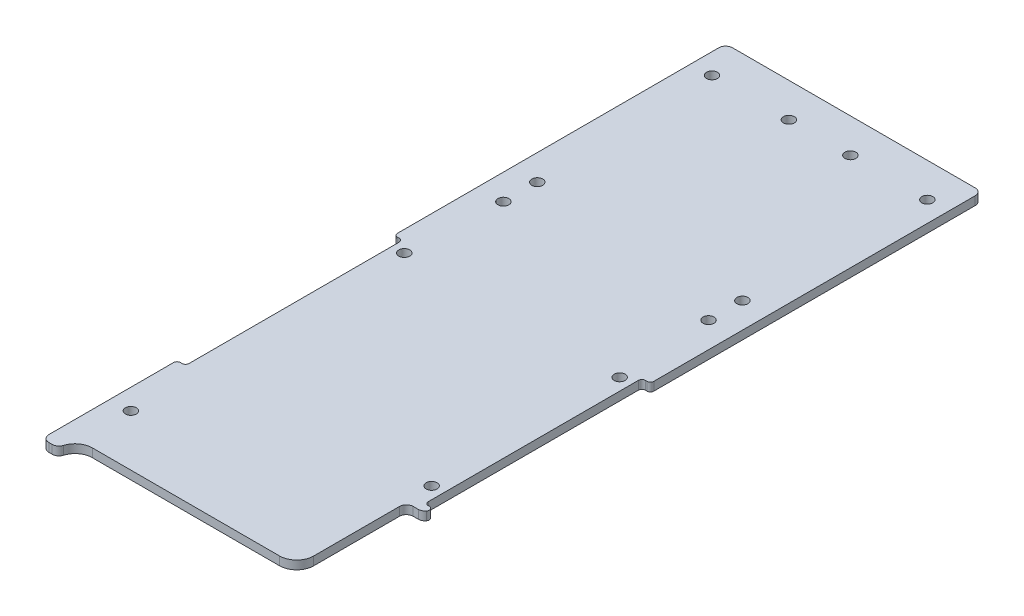
SolidWorks part; units mm, degrees
ref_plane "Front Plane" through (0, 0, 0) normal (0, 0, 1) x (1, 0, 0)
ref_plane "Top Plane" through (0, 0, 0) normal (0, 1, 0) x (1, 0, 0)
ref_plane "Right Plane" through (0, 0, 0) normal (1, 0, 0) x (0, 0, -1)
sketch "Sketch1" plane through (0, 0, 0) normal (0, 1, 0) x (1, 0, 0)
  line L0 (-39.9997, 0) -> (-39.9997, 114.3) construction
  line L1 (-47.625, 127) -> (47.625, 127)
  line L2 (-47.625, 127) -> (-47.625, -127)
  line L3 (-47.625, -127) -> (47.625, -127)
  line L4 (47.625, 127) -> (47.625, -127)
  line L5 (-47.625, 127) -> (47.625, -127) construction
  line L6 (-47.625, -127) -> (47.625, 127) construction
  line L7 (0, 0) -> (0, 127) construction
  line L8 (-39.9997, 0) -> (-39.9997, -101.6) construction
  line L9 (-39.9997, 0) -> (0, 0) construction
  line L10 (-41.275, -127) -> (-41.275, -120.65)
  line L11 (-41.275, -120.65) -> (41.275, -120.65)
  line L12 (41.275, -120.65) -> (41.275, -127)
  line L13 (-39.9997, 114.3) -> (-11.4247, 114.3) construction
  line L14 (39.9997, 114.3) -> (11.4247, 114.3) construction
  circle A0 centre (-39.9997, 114.3) radius 2.032
  circle A1 centre (-39.9997, 0) radius 2.032
  circle A2 centre (-39.9997, -101.6) radius 2.032
  circle A3 centre (39.9997, -101.6) radius 2.032
  circle A4 centre (39.9997, 0) radius 2.032
  circle A5 centre (39.9997, 114.3) radius 2.032
  circle A6 centre (-11.4247, 114.3) radius 2.032
  circle A7 centre (11.4247, 114.3) radius 2.032
  circle A8 centre (-39.9997, -69.85) radius 2.032
  circle A9 centre (39.9997, -69.85) radius 2.032
  point P0 (0, 0)
  dimension "D4" = 4.064
  dimension "D10" = 28.575
  dimension "D1" = 95.25
  dimension "D2" = 254
  dimension "D3" = 7.6253
  dimension "D5" = 12.7
  dimension "D6" = 25.4
  dimension "D7" = 6.35
  dimension "D8" = 6.35
  dimension "D9" = 6.35
  dimension "D11" = 69.85
extrude "Boss-Extrude1" add sketch "Sketch1" along normal blind 3.175 contours L4 L1 L2 L3 A4 A0 A1 A2 A3 A5 | A8 | A3
fillet "Fillet1" radius 2.54 4 edges at (-47.625, 1.5875, -127) (47.625, 1.5875, -127) (47.625, 1.5875, 127) (-47.625, 1.5875, 127)
fillet "Fillet2" radius 2.54 2 edges at (41.275, 1.5875, 127) (-41.275, 1.5875, 127)
fillet "Fillet3" radius 6.35 2 edges at (41.275, 1.5875, 120.65) (-41.275, 1.5875, 120.65)
sketch "Sketch2" plane through (0, 0, 0) normal (0, -1, 0) x (1, 0, 0)
  line L1 (43.815, 127) -> (45.085, 127) construction
  line L2 (40.6451, 123.5787) -> (40.6451, 79.8881)
  line L3 (40.6451, 79.8881) -> (47.625, 79.8881)
  line L11 (47.625, -124.46) -> (47.625, 124.46) construction
  line L12 (43.815, 127) -> (45.085, 127)
  line L13 (47.625, 79.8881) -> (47.625, 124.46)
  arc A0 (35.2956, 120.65) -> (41.3809, 125.1857) centre (35.2956, 127) ccw construction
  arc A1 (43.815, 127) -> (41.3809, 125.1857) centre (43.815, 124.46) ccw construction
  arc A2 (47.625, 124.46) -> (45.085, 127) centre (45.085, 124.46) ccw construction
  arc A3 (40.6451, 123.5787) -> (41.3809, 125.1857) centre (35.2956, 127) ccw
  arc A4 (43.815, 127) -> (41.3809, 125.1857) centre (43.815, 124.46) ccw
  arc A5 (47.625, 124.46) -> (45.085, 127) centre (45.085, 124.46) ccw
  dimension "D2" = 47.1119
  dimension "D1" = 6.9799
extrude "Cut-Extrude1" cut sketch "Sketch2" against normal through all contours L12 A5 L13 L3 L2 A3 A4
fillet "Fillet4" radius 6.35 1 edges at (40.6451, 1.5875, 123.5787)
fillet "Fillet5" radius 2.54 2 edges at (47.625, 1.5875, 79.8881) (40.6451, 1.5875, 79.8881)
sketch "Sketch3" plane through (0, 0, 0) normal (0, -1, 0) x (1, 0, 0)
  line L0 (-36.3001, -49.7791) -> (-39.9069, -49.7791) construction
  line L1 (-40.4149, -49.276) -> (-40.4149, -45.7043) construction
  line L2 (-35.7921, -45.7043) -> (-35.7921, -49.276) construction
  line L3 (-39.9069, -45.2013) -> (-36.3001, -45.2013) construction
  line L4 (-36.3001, -37.2027) -> (-39.9069, -37.2027) construction
  line L5 (-35.7921, -33.1279) -> (-35.7921, -36.6996) construction
  line L6 (-40.4149, -36.6996) -> (-40.4149, -33.1279) construction
  line L7 (-39.9069, -32.6249) -> (-36.3001, -32.6249) construction
  line L8 (36.2931, -32.6249) -> (39.8999, -32.6249) construction
  line L9 (40.4079, -33.1279) -> (40.4079, -36.6996) construction
  line L10 (39.8999, -37.2027) -> (36.2931, -37.2027) construction
  line L11 (35.7851, -36.6996) -> (35.7851, -33.1279) construction
  line L12 (36.2931, -45.2013) -> (39.8999, -45.2013) construction
  line L13 (35.7851, -49.276) -> (35.7851, -45.7043) construction
  line L14 (40.4079, -45.7043) -> (40.4079, -49.276) construction
  line L15 (39.8999, -49.7791) -> (36.2931, -49.7791) construction
  line L16 (-36.3001, -49.7791) -> (-39.9069, -49.7791)
  line L17 (-40.4149, -49.276) -> (-40.4149, -45.7043)
  line L18 (-35.7921, -45.7043) -> (-35.7921, -49.276)
  line L19 (-39.9069, -45.2013) -> (-36.3001, -45.2013)
  line L20 (-36.3001, -37.2027) -> (-39.9069, -37.2027)
  line L21 (-35.7921, -33.1279) -> (-35.7921, -36.6996)
  line L22 (-40.4149, -36.6996) -> (-40.4149, -33.1279)
  line L23 (-39.9069, -32.6249) -> (-36.3001, -32.6249)
  line L24 (36.2931, -32.6249) -> (39.8999, -32.6249)
  line L25 (40.4079, -33.1279) -> (40.4079, -36.6996)
  line L26 (39.8999, -37.2027) -> (36.2931, -37.2027)
  line L27 (35.7851, -36.6996) -> (35.7851, -33.1279)
  line L28 (36.2931, -45.2013) -> (39.8999, -45.2013)
  line L29 (35.7851, -49.276) -> (35.7851, -45.7043)
  line L30 (40.4079, -45.7043) -> (40.4079, -49.276)
  line L31 (39.8999, -49.7791) -> (36.2931, -49.7791)
  line L32 (-47.625, -25.836) -> (47.625, -25.836)
  line L33 (-47.625, -124.46) -> (-47.625, 124.46) construction
  line L34 (47.625, -124.46) -> (47.625, 77.3481) construction
  line L35 (0, -25.836) -> (0, -56.0686) construction
  line L1362 (-40.4149, -34.9138) -> (-35.7921, -34.9138)
  line L1857 (-38.1035, -32.6249) -> (-38.1035, -37.2027)
  line L1858 (-38.1035, -45.2013) -> (-38.1035, -49.7791)
  line L1859 (-40.4149, -47.4902) -> (-35.7921, -47.4902)
  circle A0 centre (-38.1035, -34.9138) radius 2.032
  circle A1 centre (-38.1035, -47.4902) radius 2.032
  circle A2 centre (38.1035, -47.4902) radius 2.032
  circle A3 centre (38.1035, -34.9138) radius 2.032
  ellipse E0 centre (-39.9069, -45.7043) end of major axis (-39.3989, -45.7043) minor radius 0.5031 (-39.9069, -45.2013) -> (-40.4149, -45.7043) ccw construction
  ellipse E1 centre (-39.9069, -49.276) end of major axis (-39.3989, -49.276) minor radius 0.5031 (-40.4149, -49.276) -> (-39.9069, -49.7791) ccw construction
  ellipse E6 centre (-36.3001, -49.276) end of major axis (-35.7921, -49.276) minor radius 0.5031 (-36.3001, -49.7791) -> (-35.7921, -49.276) ccw construction
  ellipse E7 centre (-36.3001, -45.7043) end of major axis (-35.7921, -45.7043) minor radius 0.5031 (-35.7921, -45.7043) -> (-36.3001, -45.2013) ccw construction
  ellipse E8 centre (-39.9069, -36.6996) end of major axis (-39.3989, -36.6996) minor radius 0.5031 (-40.4149, -36.6996) -> (-39.9069, -37.2027) ccw construction
  ellipse E9 centre (-36.3001, -36.6996) end of major axis (-35.7921, -36.6996) minor radius 0.5031 (-36.3001, -37.2027) -> (-35.7921, -36.6996) ccw construction
  ellipse E10 centre (-36.3001, -33.1279) end of major axis (-35.7921, -33.1279) minor radius 0.5031 (-35.7921, -33.1279) -> (-36.3001, -32.6249) ccw construction
  ellipse E11 centre (-39.9069, -33.1279) end of major axis (-39.3989, -33.1279) minor radius 0.5031 (-39.9069, -32.6249) -> (-40.4149, -33.1279) ccw construction
  ellipse E12 centre (39.8999, -33.1279) end of major axis (40.4079, -33.1279) minor radius 0.5031 (40.4079, -33.1279) -> (39.8999, -32.6249) ccw construction
  ellipse E13 centre (36.2931, -33.1279) end of major axis (36.8011, -33.1279) minor radius 0.5031 (36.2931, -32.6249) -> (35.7851, -33.1279) ccw construction
  ellipse E14 centre (39.8999, -36.6996) end of major axis (40.4079, -36.6996) minor radius 0.5031 (39.8999, -37.2027) -> (40.4079, -36.6996) ccw construction
  ellipse E15 centre (36.2931, -36.6996) end of major axis (36.8011, -36.6996) minor radius 0.5031 (35.7851, -36.6996) -> (36.2931, -37.2027) ccw construction
  ellipse E16 centre (36.2931, -45.7043) end of major axis (36.8011, -45.7043) minor radius 0.5031 (36.2931, -45.2013) -> (35.7851, -45.7043) ccw construction
  ellipse E17 centre (36.2931, -49.276) end of major axis (36.8011, -49.276) minor radius 0.5031 (35.7851, -49.276) -> (36.2931, -49.7791) ccw construction
  ellipse E18 centre (39.8999, -45.7043) end of major axis (40.4079, -45.7043) minor radius 0.5031 (40.4079, -45.7043) -> (39.8999, -45.2013) ccw construction
  ellipse E19 centre (39.8999, -49.276) end of major axis (40.4079, -49.276) minor radius 0.5031 (39.8999, -49.7791) -> (40.4079, -49.276) ccw construction
  ellipse E20 centre (-39.9069, -45.7043) end of major axis (-39.3989, -45.7043) minor radius 0.5031 (-39.9069, -45.2013) -> (-40.4149, -45.7043) ccw
  ellipse E21 centre (-39.9069, -49.276) end of major axis (-39.3989, -49.276) minor radius 0.5031 (-40.4149, -49.276) -> (-39.9069, -49.7791) ccw
  ellipse E22 centre (-36.3001, -49.276) end of major axis (-35.7921, -49.276) minor radius 0.5031 (-36.3001, -49.7791) -> (-35.7921, -49.276) ccw
  ellipse E23 centre (-36.3001, -45.7043) end of major axis (-35.7921, -45.7043) minor radius 0.5031 (-35.7921, -45.7043) -> (-36.3001, -45.2013) ccw
  ellipse E24 centre (-39.9069, -36.6996) end of major axis (-39.3989, -36.6996) minor radius 0.5031 (-40.4149, -36.6996) -> (-39.9069, -37.2027) ccw
  ellipse E25 centre (-36.3001, -36.6996) end of major axis (-35.7921, -36.6996) minor radius 0.5031 (-36.3001, -37.2027) -> (-35.7921, -36.6996) ccw
  ellipse E26 centre (-36.3001, -33.1279) end of major axis (-35.7921, -33.1279) minor radius 0.5031 (-35.7921, -33.1279) -> (-36.3001, -32.6249) ccw
  ellipse E27 centre (-39.9069, -33.1279) end of major axis (-39.3989, -33.1279) minor radius 0.5031 (-39.9069, -32.6249) -> (-40.4149, -33.1279) ccw
  ellipse E28 centre (39.8999, -33.1279) end of major axis (40.4079, -33.1279) minor radius 0.5031 (40.4079, -33.1279) -> (39.8999, -32.6249) ccw
  ellipse E29 centre (36.2931, -33.1279) end of major axis (36.8011, -33.1279) minor radius 0.5031 (36.2931, -32.6249) -> (35.7851, -33.1279) ccw
  ellipse E30 centre (39.8999, -36.6996) end of major axis (40.4079, -36.6996) minor radius 0.5031 (39.8999, -37.2027) -> (40.4079, -36.6996) ccw
  ellipse E31 centre (36.2931, -36.6996) end of major axis (36.8011, -36.6996) minor radius 0.5031 (35.7851, -36.6996) -> (36.2931, -37.2027) ccw
  ellipse E32 centre (36.2931, -45.7043) end of major axis (36.8011, -45.7043) minor radius 0.5031 (36.2931, -45.2013) -> (35.7851, -45.7043) ccw
  ellipse E33 centre (36.2931, -49.276) end of major axis (36.8011, -49.276) minor radius 0.5031 (35.7851, -49.276) -> (36.2931, -49.7791) ccw
  ellipse E34 centre (39.8999, -45.7043) end of major axis (40.4079, -45.7043) minor radius 0.5031 (40.4079, -45.7043) -> (39.8999, -45.2013) ccw
  ellipse E35 centre (39.8999, -49.276) end of major axis (40.4079, -49.276) minor radius 0.5031 (39.8999, -49.7791) -> (40.4079, -49.276) ccw
  dimension "D2" = 4.064
extrude "Cut-Extrude2" cut sketch "Sketch3" against normal through all contours A0 | A1 | A2 | A3
sketch "Sketch4" plane through (0, 3.175, 0) normal (0, 1, 0) x (1, 0, 0)
  line L11 (-47.625, 124.46) -> (-47.625, -124.46) construction
  line L12 (-47.625, -76.835) -> (-44.45, -76.835)
  line L13 (-47.625, -76.835) -> (-47.625, 3.81)
  line L15 (-47.625, 3.81) -> (-44.45, 3.81)
  line L16 (-44.45, -76.835) -> (-44.45, 3.81)
  line L17 (47.625, 124.46) -> (47.625, -77.3481) construction
  line L18 (47.625, -76.835) -> (44.45, -76.835)
  line L19 (47.625, -76.835) -> (47.625, 3.81)
  line L20 (47.625, 3.81) -> (44.45, 3.81)
  line L45 (44.45, -76.835) -> (44.45, 3.81)
  line L47 (43.1851, -79.8881) -> (45.085, -79.8881) construction
  dimension "D1" = 3.175
  dimension "D2" = 80.645
  dimension "D3" = 3.0531
extrude "Cut-Extrude3" cut sketch "Sketch4" against normal through all and the other way through all
fillet "Fillet6" radius 1.27 8 edges at (-44.45, 1.5875, -3.81) (-47.625, 1.5875, -3.81) (-47.625, 1.5875, 76.835) (-44.45, 1.5875, 76.835) (44.45, 1.5875, 76.835) (47.625, 1.5875, 76.835) (44.45, 1.5875, -3.81) (47.625, 1.5875, -3.81)
